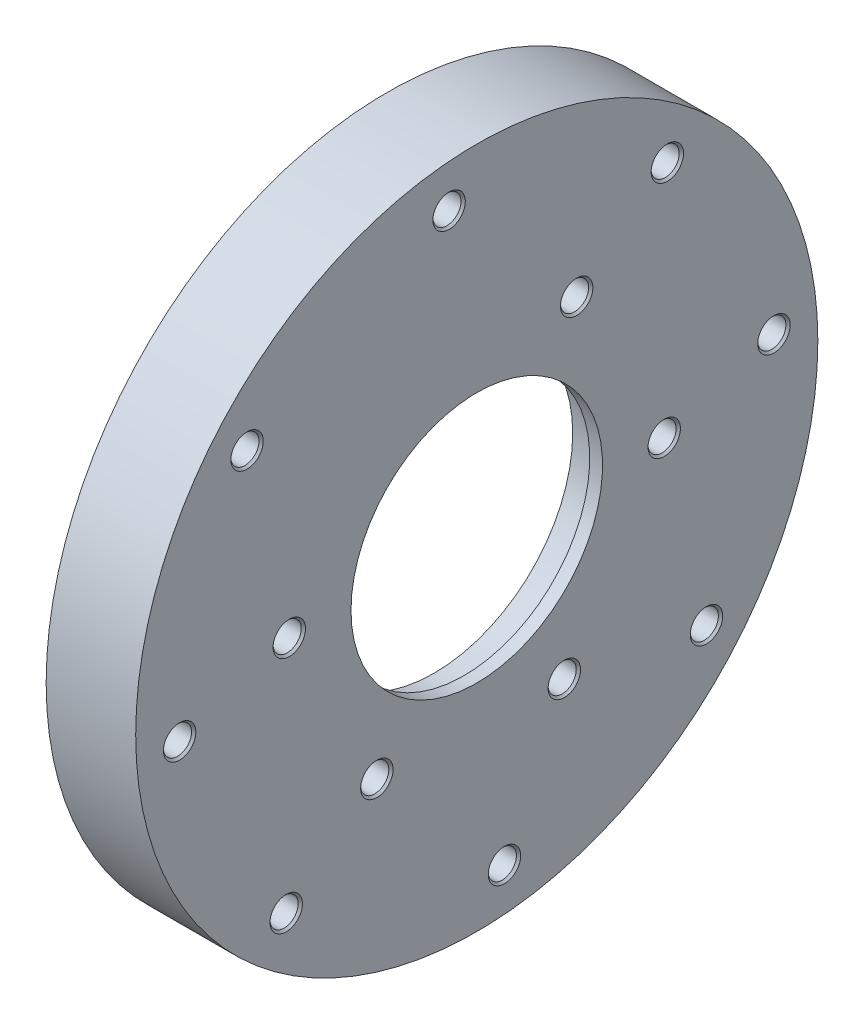
SolidWorks part; units mm, degrees
ref_plane "Front Plane" through (0, 0, 0) normal (0, 0, 1) x (1, 0, 0)
ref_plane "Top Plane" through (0, 0, 0) normal (0, 1, 0) x (1, 0, 0)
ref_plane "Right Plane" through (0, 0, 0) normal (1, 0, 0) x (0, 0, -1)
sketch "Sketch2" plane through (0, 0, 0) normal (0, 0, 1) x (1, 0, 0)
  line L0 (0, 0) -> (80.4799, 0) construction
  line L1 (0, 80) -> (0, 52.5)
  line L2 (0, 52.5) -> (11, 52.5)
  line L3 (11, 52.5) -> (11, 32.5)
  line L4 (11, 32.5) -> (18, 32.5)
  line L5 (18, 32.5) -> (18, 29.5)
  line L6 (18, 29.5) -> (21, 29.5)
  line L7 (21, 29.5) -> (21, 80)
  line L8 (21, 80) -> (0, 80)
  dimension "D1" = 80
  dimension "D2" = 32.5
  dimension "D3" = 52.5
  dimension "D4" = 18
  dimension "D5" = 3
  dimension "D6" = 7
  dimension "D7" = 3
revolve "Revolve1" add sketch "Sketch2" angle 360 about L0
sketch "Sketch3" plane through (0, 0, 0) normal (-1, 0, 0) x (0, 0, 1)
  circle A0 centre (0, 0) radius 60 construction
  circle A1 centre (0, 60) radius 2.5
  circle A2 centre (12.0779, 58.7718) radius 2.5
  circle A3 centre (23.6614, 55.1375) radius 2.5
  circle A4 centre (34.2761, 49.2458) radius 2.5
  circle A5 centre (43.4876, 41.338) radius 2.5
  circle A6 centre (50.9187, 31.7378) radius 2.5
  circle A7 centre (56.2651, 20.8383) radius 2.5
  circle A8 centre (59.3081, 9.0857) radius 2.5
  circle A9 centre (59.923, -3.039) radius 2.5
  circle A10 centre (58.0846, -15.0392) radius 2.5
  circle A11 centre (53.8683, -26.4236) radius 2.5
  circle A12 centre (47.4465, -36.7264) radius 2.5
  circle A13 centre (39.0823, -45.5255) radius 2.5
  circle A14 centre (29.1181, -52.4608) radius 2.5
  circle A15 centre (17.9618, -57.2484) radius 2.5
  circle A16 centre (6.0701, -59.6922) radius 2.5
  circle A17 centre (-6.0701, -59.6922) radius 2.5
  circle A18 centre (-17.9618, -57.2484) radius 2.5
  circle A19 centre (-29.1181, -52.4608) radius 2.5
  circle A20 centre (-39.0823, -45.5255) radius 2.5
  circle A21 centre (-47.4465, -36.7264) radius 2.5
  circle A22 centre (-53.8683, -26.4236) radius 2.5
  circle A23 centre (-58.0846, -15.0392) radius 2.5
  circle A24 centre (-59.923, -3.039) radius 2.5
  circle A25 centre (-59.3081, 9.0857) radius 2.5
  circle A26 centre (-56.2651, 20.8383) radius 2.5
  circle A27 centre (-50.9187, 31.7378) radius 2.5
  circle A28 centre (-43.4876, 41.338) radius 2.5
  circle A29 centre (-34.2761, 49.2458) radius 2.5
  circle A30 centre (-23.6614, 55.1375) radius 2.5
  circle A31 centre (-12.0779, 58.7718) radius 2.5
  point P67 (0, 0)
  dimension "D1" = 120
  dimension "D2" = 5
  dimension "D3" = 31
extrude "Cut-Extrude1" cut sketch "Sketch3" against normal blind 4
sketch "Sketch4" [suppressed] plane through (21, 0, 0) normal (1, 0, 0) x (0, 0, -1)
  circle A0 centre (-38.0255, -58.7712) radius 5.5
  circle A1 centre (-68.4457, -14.6694) radius 5.5
  circle A2 centre (-58.7712, 38.0255) radius 5.5
  circle A3 centre (-14.6694, 68.4457) radius 5.5
  circle A4 centre (38.0255, 58.7712) radius 5.5
  circle A5 centre (68.4457, 14.6694) radius 5.5
  circle A6 centre (58.7712, -38.0255) radius 5.5
  circle A7 centre (14.6694, -68.4457) radius 5.5
  point P16 (0, 0)
  dimension "D2" = 11
  dimension "D1" = 8
extrude "Cut-Extrude2" [suppressed] cut sketch "Sketch4" against normal blind 4
sketch "Sketch5" [suppressed] plane through (21, 0, 0) normal (1, 0, 0) x (0, 0, -1)
  circle A0 centre (-38.0255, -58.7712) radius 3
  circle A1 centre (-68.4457, -14.6694) radius 3
  circle A2 centre (-58.7712, 38.0255) radius 3
  circle A3 centre (-14.6694, 68.4457) radius 3
  circle A4 centre (38.0255, 58.7712) radius 3
  circle A5 centre (68.4457, 14.6694) radius 3
  circle A6 centre (58.7712, -38.0255) radius 3
  circle A7 centre (14.6694, -68.4457) radius 3
  point P16 (0, 0)
  dimension "D2" = 6
  dimension "D1" = 8
extrude "Cut-Extrude3" [suppressed] cut sketch "Sketch5" against normal through all
sketch "Sketch6" plane through (0, 0, 0) normal (-1, 0, 0) x (0, 0, 1)
  circle A0 centre (53.8756, 44.6925) radius 3
  circle A1 centre (69.6982, -6.4934) radius 3
  circle A2 centre (44.6925, -53.8756) radius 3
  circle A3 centre (-6.4934, -69.6982) radius 3
  circle A4 centre (-53.8756, -44.6925) radius 3
  circle A5 centre (-69.6982, 6.4934) radius 3
  circle A6 centre (-44.6925, 53.8756) radius 3
  circle A7 centre (6.4934, 69.6982) radius 3
  point P15 (0, 0)
  dimension "D2" = 6
  dimension "D1" = 8
extrude "Cut-Extrude4" cut sketch "Sketch6" against normal blind 11
sketch "Sketch7" plane through (21, 0, 0) normal (-1, 0, 0) x (0, 0, 1)
  circle A0 centre (53.8756, 44.6925) radius 3.3
  circle A1 centre (69.6982, -6.4934) radius 3.3
  circle A2 centre (44.6925, -53.8756) radius 3.3
  circle A3 centre (-6.4934, -69.6982) radius 3.3
  circle A4 centre (-53.8756, -44.6925) radius 3.3
  circle A5 centre (-69.6982, 6.4934) radius 3.3
  circle A6 centre (-44.6925, 53.8756) radius 3.3
  circle A7 centre (6.4934, 69.6982) radius 3.3
  point P15 (0, 0)
  dimension "D1" = 6.6
  dimension "D2" = 8
extrude "Cut-Extrude5" cut sketch "Sketch7" along normal blind 10
sketch "Sketch8" [suppressed] plane through (21, 0, 0) normal (1, 0, 0) x (0, 0, -1)
  circle A0 centre (-23.7966, 67.4351) radius 1
  dimension "D1" = 2
extrude "Cut-Extrude6" [suppressed] cut sketch "Sketch8" against normal blind 2
sketch "Sketch9" plane through (0, 0, 0) normal (-1, 0, 0) x (0, 0, 1)
  circle A0 centre (2.5177, -71.4663) radius 1
  dimension "D1" = 2
extrude "Cut-Extrude7" cut sketch "Sketch9" against normal blind 2
sketch "Sketch10" plane through (21, 0, 0) normal (1, 0, 0) x (0, 0, -1)
  line L0 (69.6982, 6.4934) -> (-44.6925, -53.8756) construction
  line L1 (23.4319, 37.2417) -> (0, 0) construction
  line L2 (0, 0) -> (43.9682, -1.6717) construction
  line L3 (0, 0) -> (-23.4319, -37.2417) construction
  circle A0 centre (0, 0) radius 44 construction
  circle A1 centre (23.4319, 37.2417) radius 3.3
  circle A2 centre (20.5363, -38.9135) radius 3.3
  circle A3 centre (-43.9682, 1.6717) radius 3.3
  circle A4 centre (-23.4319, -37.2417) radius 3.3
  circle A5 centre (43.9682, -1.6717) radius 3.3
  point P15 (0, 0)
  dimension "D1" = 6.6
  dimension "D2" = 88
  dimension "D3" = 30
  dimension "D5" = 60
  dimension "D6" = 120
  dimension "D4" = 3
extrude "Cut-Extrude8" cut sketch "Sketch10" against normal up to next
chamfer "Chamfer1" distance 0.5 angle 45 13 edges at (21, -53.8756, 47.9925) (21, -69.6982, -3.1934) (21, -44.6925, -50.5756) (21, 6.4934, -66.3982) (21, 44.6925, 57.1756) (21, -6.4934, 72.9982) (21, 1.6717, 40.6682) (21, -38.9135, -23.8363) (21, 37.2417, -26.7319) (21, -37.2417, 20.1319) (21, -1.6717, -47.2682) (21, 69.6982, 9.7934) (21, 53.8756, -41.3925)
equation "\"R_ROLL\"= 5mm"
equation "\"D_SUN\"= 120mm"
equation "\"NUM_ROLL\"= 31"
equation "\"RHO\"= 1mm"
equation "\"D_SHAFT\"= 28mm"
equation "\"D_OUTPUT\"= 80mm"
equation "\"NUM_OUT\"= 8"
equation "\"R_OUT_ROLL\"= 5mm"
equation "\"D1@Sketch3\"=\"D_SUN\""
